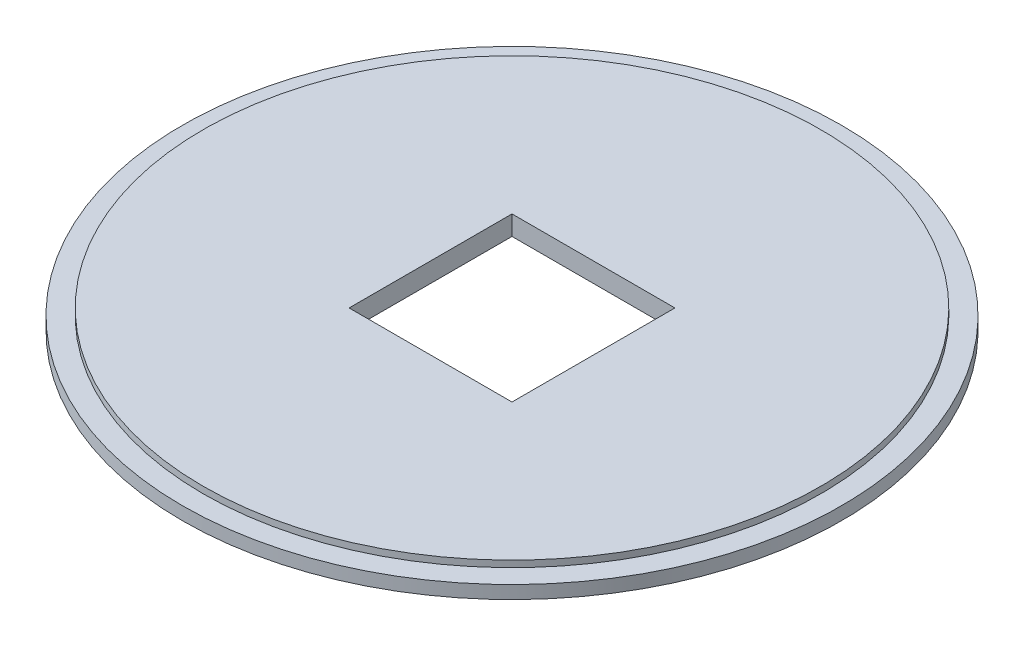
SolidWorks part; units mm, degrees
ref_plane "Front Plane" through (0, 0, 0) normal (0, 0, 1) x (1, 0, 0)
ref_plane "Top Plane" through (0, 0, 0) normal (0, 1, 0) x (1, 0, 0)
ref_plane "Right Plane" through (0, 0, 0) normal (1, 0, 0) x (0, 0, -1)
sketch "Sketch1" plane through (0, 0, 0) normal (0, 0, 1) x (1, 0, 0)
  line L0 (0, 0) -> (-101.15, 0)
  line L1 (55, 0) -> (-55, 0) construction
  line L2 (-101.15, 0) -> (-101.15, 4)
  line L3 (-101.15, 4) -> (-94.8, 4)
  line L4 (-94.8, 4) -> (-94.8, 6)
  line L5 (-94.8, 6) -> (0, 6)
  line L6 (0, -55) -> (0, 55) construction
  line L7 (0, 6) -> (0, 0)
  dimension "D1" = 6
  dimension "D2" = 101.15
  dimension "D3" = 6.35
  dimension "D4" = 4
revolve "Revolve1" add sketch "Sketch1" angle 360 about L7
sketch "Sketch2" plane through (0, 0, 0) normal (0, 1, 0) x (1, 0, 0)
  line L1 (-25, -25) -> (25, -25)
  line L2 (-25, -25) -> (-25, 25)
  line L3 (-25, 25) -> (25, 25)
  line L4 (25, -25) -> (25, 25)
  line L5 (-25, -25) -> (25, 25) construction
  line L6 (-25, 25) -> (25, -25) construction
  point P0 (0, 0)
  dimension "D1" = 50
  dimension "D2" = 50
extrude "Cut-Extrude1" cut sketch "Sketch2" along normal blind 10
